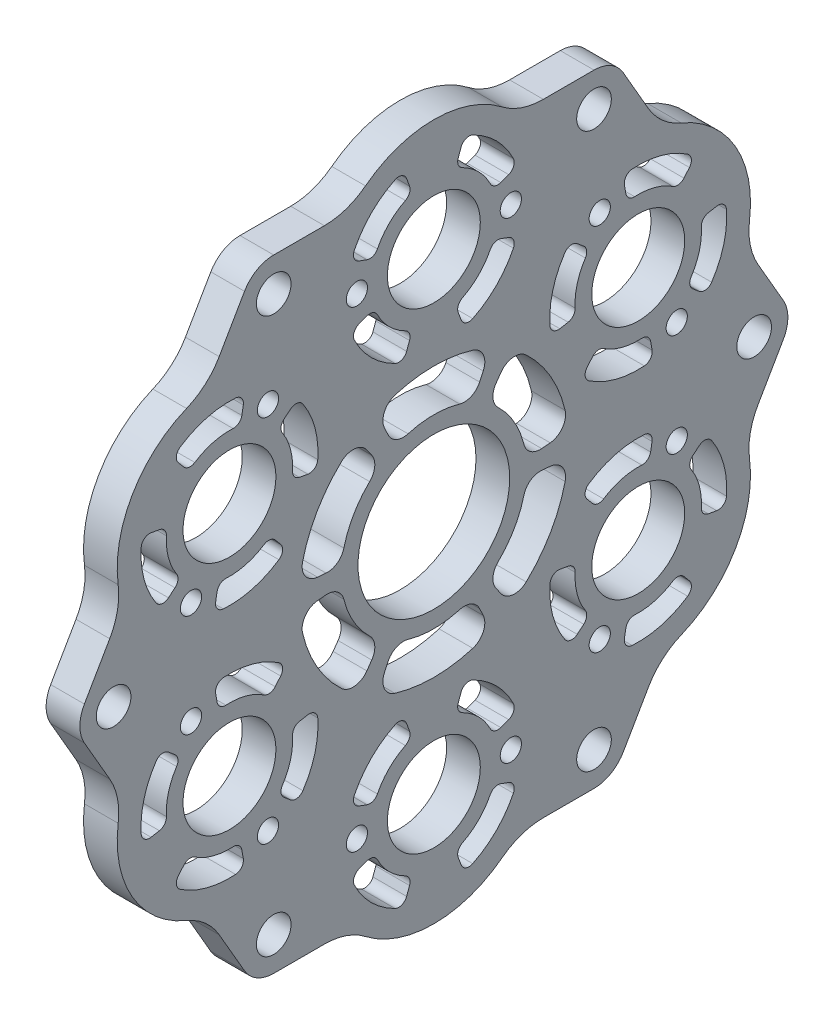
SolidWorks part; units mm, degrees
material "6061-T6 (SS)"
ref_plane "Front Plane" through (0, 0, 0) normal (0, 0, 1) x (1, 0, 0)
ref_plane "Top Plane" through (0, 0, 0) normal (0, 1, 0) x (1, 0, 0)
ref_plane "Right Plane" through (0, 0, 0) normal (1, 0, 0) x (0, 0, -1)
sketch "Sketch1" plane through (0, 0, 0) normal (1, 0, 0) x (0, 0, -1)
  line L0 (-147.1043, -3.175) -> (-116.9418, -55.418)
  line L1 (-111.4425, -58.593) -> (-51.1175, -58.593)
  line L2 (-45.6182, -55.418) -> (-15.4557, -3.175)
  line L3 (-45.6182, 55.418) -> (-15.4557, 3.175)
  line L4 (-111.4425, 58.593) -> (-51.1175, 58.593)
  line L5 (-116.9418, 55.418) -> (-147.1043, 3.175)
  circle A0 centre (-51.1175, 52.243) radius 3.2639 construction
  circle A1 centre (-20.955, 0) radius 3.2639 construction
  circle A2 centre (-51.1175, -52.243) radius 3.2639 construction
  circle A3 centre (-111.4425, -52.243) radius 3.2639 construction
  circle A4 centre (-141.605, 0) radius 3.2639 construction
  circle A5 centre (-111.4425, 52.243) radius 3.2639 construction
  circle A6 centre (-51.1175, 52.243) radius 3.2639
  circle A7 centre (-20.955, 0) radius 3.2639
  circle A8 centre (-51.1175, -52.243) radius 3.2639
  circle A9 centre (-111.4425, -52.243) radius 3.2639
  circle A10 centre (-141.605, 0) radius 3.2639
  circle A11 centre (-111.4425, 52.243) radius 3.2639
  circle A12 centre (-111.4425, 52.243) radius 6.35
  circle A13 centre (-51.1175, 52.243) radius 6.35
  circle A14 centre (-20.955, 0) radius 6.35
  circle A15 centre (-51.1175, -52.243) radius 6.35
  circle A16 centre (-111.4425, -52.243) radius 6.35
  circle A17 centre (-141.605, 0) radius 6.35
  circle A18 centre (-81.28, 44.45) radius 21.1455
  circle A20 centre (-42.7852, 22.225) radius 21.1455
  circle A21 centre (-42.7852, -22.225) radius 21.1455
  circle A22 centre (-81.28, -44.45) radius 21.1455
  circle A23 centre (-119.7748, -22.225) radius 21.1455
  circle A24 centre (-119.7748, 22.225) radius 21.1455
  circle A25 centre (-81.28, 44.45) radius 21.1455 construction
  point P32 (-81.28, 0)
  point P57 (-81.28, 0)
  dimension "D2" = 12.7
  dimension "D1" = 6
  dimension "D3" = 6
extrude "Boss-Extrude1" add sketch "Sketch1" along normal blind 6.35 contours A17 L0 A16 L1 A15 L2 A14 L3 A13 L4 A12 L5 | A17 A10 | A12 A11 | A13 A6 | A15 A8 | A16 A9 | A14 A7 | L5 A24 | L5 A24 | L4 A18 | L4 A18 | L3 A20 | L3 A20 | L2 A21 | L2 A21 | L1 A22 | L1 A22 | L0 A23 | L0 A23
fillet "Fillet1" radius 12.7 12 edges at (3.175, -42.9101, 124.1632) (3.175, -15.6829, 139.8828) (3.175, -58.593, 65.5603) (3.175, -58.593, 96.9997) (3.175, -15.6829, 22.6772) (3.175, -42.9101, 38.3968) (3.175, 42.9101, 38.3968) (3.175, 15.6829, 22.6772) (3.175, 58.593, 96.9997) (3.175, 58.593, 65.5603) (3.175, 15.6829, 139.8828) (3.175, 42.9101, 124.1632)
sketch "Sketch2" plane through (6.35, 0, 0) normal (1, 0, 0) x (0, 0, -1)
  circle A0 centre (-119.7748, -22.225) radius 8.7503 construction
  circle A1 centre (-81.28, -44.45) radius 8.7503 construction
  circle A2 centre (-42.7852, -22.225) radius 8.7503 construction
  circle A3 centre (-42.7852, 22.225) radius 8.7503 construction
  circle A4 centre (-81.28, 44.45) radius 8.7503 construction
  circle A5 centre (-119.7748, 22.225) radius 8.7503 construction
  circle A6 centre (-119.7748, -22.225) radius 8.7503
  circle A7 centre (-81.28, -44.45) radius 8.7503
  circle A8 centre (-42.7852, -22.225) radius 8.7503
  circle A9 centre (-42.7852, 22.225) radius 8.7503
  circle A10 centre (-81.28, 44.45) radius 8.7503
  circle A11 centre (-119.7748, 22.225) radius 8.7503
  circle A12 centre (-81.28, 0) radius 14.2875 construction
  circle A13 centre (-81.28, 0) radius 14.2875
extrude "Cut-Extrude1" cut sketch "Sketch2" against normal through all
sketch "Sketch3" plane through (6.35, 0, 0) normal (1, 0, 0) x (0, 0, -1)
  line L0 (-85.3522, 55.6382) -> (-86.981, 60.1135)
  line L1 (-92.4682, 48.5222) -> (-96.9435, 50.151)
  line L2 (-92.4682, 48.5222) -> (-81.28, 44.45) construction
  line L3 (-81.28, 44.45) -> (-85.3522, 55.6382) construction
  line L4 (-81.28, 44.45) -> (-81.28, 65.0159) construction
  line L5 (-66.7804, 44.45) -> (-95.7796, 44.45) construction
  line L6 (-77.2078, 55.6382) -> (-75.579, 60.1135)
  line L7 (-70.0918, 48.5222) -> (-65.6165, 50.151)
  line L8 (-70.0918, 40.3778) -> (-65.6165, 38.749)
  line L9 (-77.2078, 33.2618) -> (-75.579, 28.7865)
  line L10 (-85.3522, 33.2618) -> (-86.981, 28.7865)
  line L11 (-92.4682, 40.3778) -> (-96.9435, 38.749)
  circle A0 centre (-66.7804, 44.45) radius 2 construction
  circle A1 centre (-95.7796, 44.45) radius 2 construction
  circle A2 centre (-66.7804, 44.45) radius 2
  circle A3 centre (-95.7796, 44.45) radius 2
  arc A4 (-86.981, 60.1135) -> (-96.9435, 50.151) centre (-81.28, 44.45) ccw
  arc A6 (-70.0918, 48.5222) -> (-77.2078, 55.6382) centre (-81.28, 44.45) ccw
  arc A7 (-85.3522, 55.6382) -> (-92.4682, 48.5222) centre (-81.28, 44.45) ccw
  arc A8 (-65.6165, 50.151) -> (-75.579, 60.1135) centre (-81.28, 44.45) ccw
  arc A9 (-77.2078, 33.2618) -> (-70.0918, 40.3778) centre (-81.28, 44.45) ccw
  arc A10 (-75.579, 28.7865) -> (-65.6165, 38.749) centre (-81.28, 44.45) ccw
  arc A11 (-92.4682, 40.3778) -> (-85.3522, 33.2618) centre (-81.28, 44.45) ccw
  arc A12 (-96.9435, 38.749) -> (-86.981, 28.7865) centre (-81.28, 44.45) ccw
  point P31 (-81.28, 44.45)
  dimension "D2" = 33.3375
  dimension "D4" = 4.7625
  dimension "D1" = 20
  dimension "D3" = 20
  dimension "D5" = 4
extrude "Cut-Extrude2" cut sketch "Sketch3" against normal through all
fillet "Fillet2" radius 1.5875 16 edges at (3.175, 50.151, 96.9435) (3.175, 60.1135, 86.981) (3.175, 55.6382, 85.3522) (3.175, 48.5222, 92.4682) (3.175, 55.6382, 77.2078) (3.175, 60.1135, 75.579) (3.175, 50.151, 65.6165) (3.175, 48.5222, 70.0918) (3.175, 28.7865, 75.579) (3.175, 38.749, 65.6165) (3.175, 40.3778, 70.0918) (3.175, 33.2618, 77.2078) (3.175, 28.7865, 86.981) (3.175, 33.2618, 85.3522) (3.175, 40.3778, 92.4682) (3.175, 38.749, 96.9435)
sketch "Sketch4" plane through (6.35, 0, 0) normal (1, 0, 0) x (0, 0, -1)
  circle A0 centre (-66.7804, 44.45) radius 2 construction
  circle A1 centre (-95.7796, 44.45) radius 2 construction
  circle A2 centre (-66.7804, 44.45) radius 2
  circle A3 centre (-95.7796, 44.45) radius 2
extrude "Cut-Extrude3" cut sketch "Sketch4" against normal through all
sketch "Sketch6" plane through (6.35, 0, 0) normal (1, 0, 0) x (0, 0, -1)
  line L0 (-81.28, 0) -> (-81.28, 25.4) construction
  line L1 (-89.8979, 18.4813) -> (-90.5764, 19.9361)
  line L2 (-72.6621, 18.4813) -> (-71.9836, 19.9361)
  line L3 (-89.8979, 18.4813) -> (-81.28, 0) construction
  line L4 (-81.28, 0) -> (-72.6621, 18.4813) construction
  arc A0 (-73.9442, 24.3176) -> (-88.6158, 24.3176) centre (-81.28, 0) ccw
  arc A1 (-76.4227, 16.7734) -> (-86.1373, 16.7734) centre (-81.28, 0) ccw
  arc A2 (-71.9836, 19.9361) -> (-73.9442, 24.3176) centre (-74.8612, 21.2779) ccw
  arc A3 (-76.4227, 16.7734) -> (-72.6621, 18.4813) centre (-75.5396, 19.8231) ccw
  arc A4 (-89.8979, 18.4813) -> (-86.1373, 16.7734) centre (-87.0204, 19.8231) ccw
  arc A5 (-90.5764, 19.9361) -> (-88.6158, 24.3176) centre (-87.6988, 21.2779) cw
  circle A6 centre (-81.28, 0) radius 14.2875 construction
  point P9 (-70.5455, 23.0202)
  point P16 (-92.0145, 23.0202)
  dimension "D2" = 3.175
  dimension "D3" = 3.175
  dimension "D4" = 7.9375
  dimension "D1" = 50
extrude "Cut-Extrude4" cut sketch "Sketch6" against normal through all contours A1 L0 A0 L1 | L0 A1 L2 A0
pattern_circular "CirPattern3" count 6 over 360 about axis through (0, 0, 81.28) along (1, 0, 0) of "Cut-Extrude3", "Cut-Extrude2", "Fillet2", "Cut-Extrude4"
